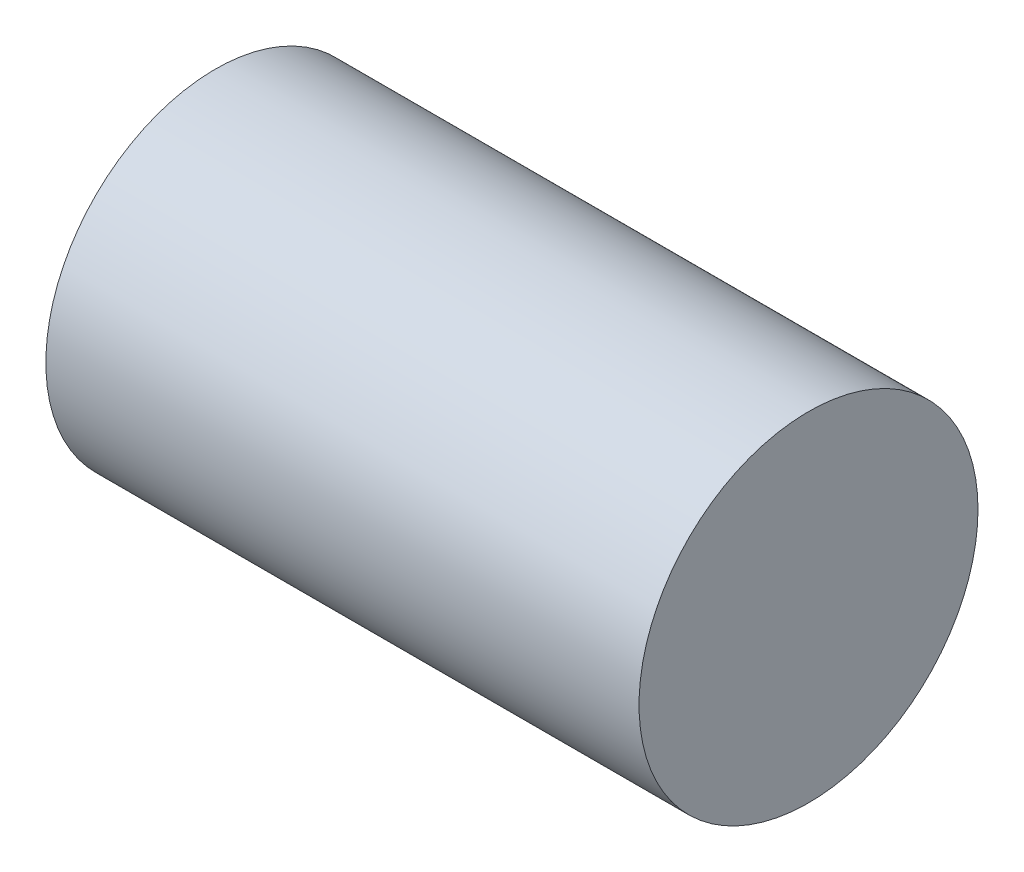
SolidWorks part; units mm, degrees
material "Acrylic (Medium-high impact)"
ref_plane "Front Plane" through (0, 0, 0) normal (0, 0, 1) x (1, 0, 0)
ref_plane "Top Plane" through (0, 0, 0) normal (0, 1, 0) x (1, 0, 0)
ref_plane "Right Plane" through (0, 0, 0) normal (1, 0, 0) x (0, 0, -1)
sketch "Sketch1" plane through (0, 0, 0) normal (1, 0, 0) x (0, 0, -1)
  circle A0 centre (0, 0) radius 200
  dimension "D1" = 400
extrude "Boss-Extrude1" add sketch "Sketch1" along normal blind 700
